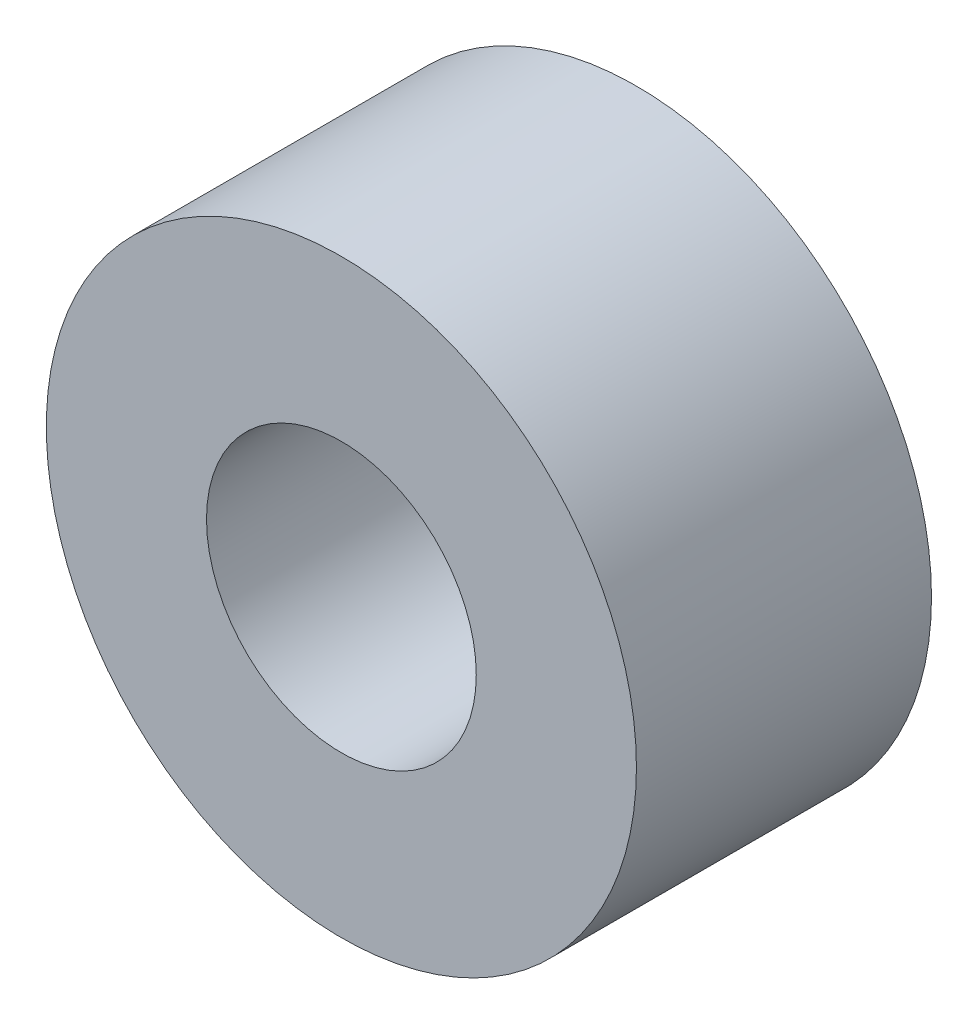
SolidWorks part; units mm, degrees
ref_plane "正面" through (0, 0, 0) normal (0, 0, 1) x (1, 0, 0)
ref_plane "平面" through (0, 0, 0) normal (0, 1, 0) x (1, 0, 0)
ref_plane "右側面" through (0, 0, 0) normal (1, 0, 0) x (0, 0, -1)
sketch "ｽｹｯﾁ1" plane through (0, 0, 0) normal (0, 0, 1) x (1, 0, 0)
  circle A0 centre (0, 0) radius 3.5
  circle A2 centre (0, 0) radius 1.6
  dimension "D1" = 3.2
  dimension "D2" = 7
extrude "ﾎﾞｽ - 押し出し1" add sketch "ｽｹｯﾁ1" along normal blind 3.5
